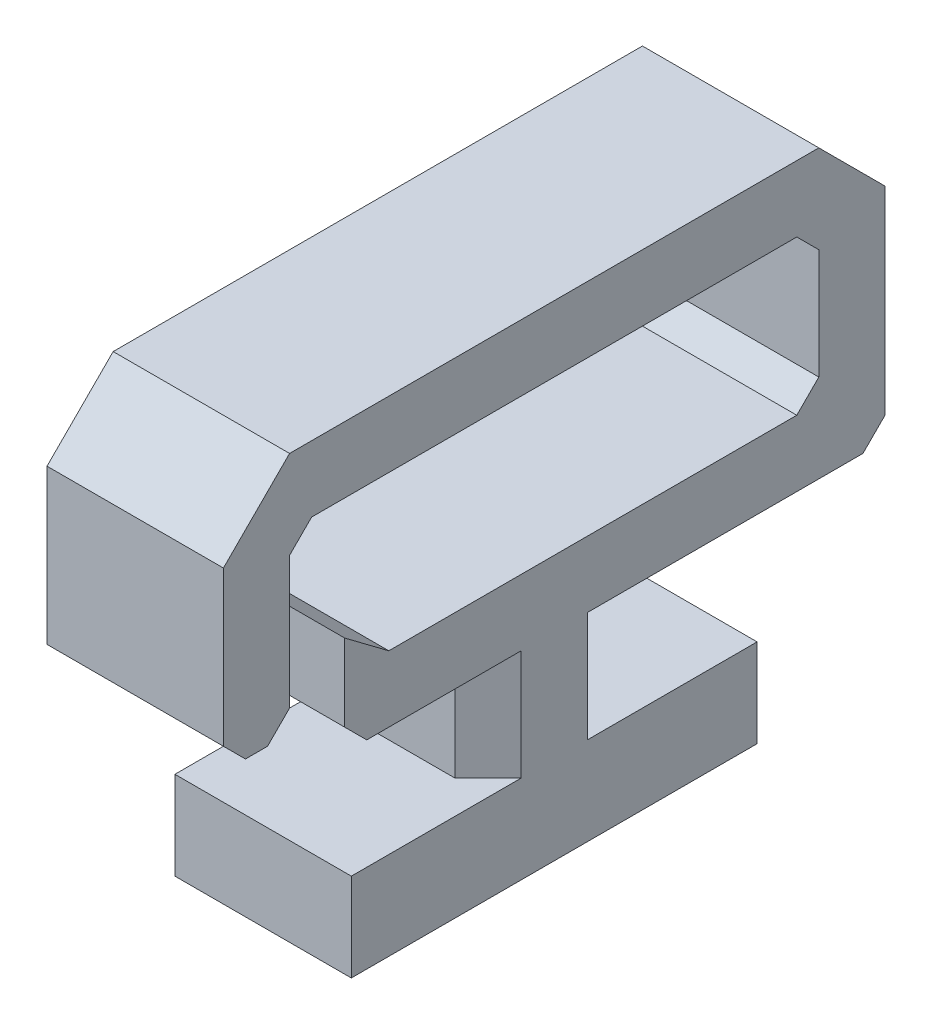
SolidWorks part; units mm, degrees
ref_plane "Front Plane" through (0, 0, 0) normal (0, 0, 1) x (1, 0, 0)
ref_plane "Top Plane" through (0, 0, 0) normal (0, 1, 0) x (1, 0, 0)
ref_plane "Right Plane" through (0, 0, 0) normal (1, 0, 0) x (0, 0, -1)
sketch "Sketch1" plane through (0, 0, 0) normal (1, 0, 0) x (0, 0, -1)
  line L0 (-4.6, 0) -> (4.6, 0)
  line L1 (-4.6, 0) -> (-4.6, 2)
  line L2 (-4.6, 2) -> (-1.5, 2)
  line L3 (4.6, 2) -> (4.6, 0)
  line L4 (0, 0) -> (0, 69.0546) construction
  line L5 (-1.5, 2) -> (-1.5, 4.5)
  line L6 (-6, 6) -> (-6, 4.5)
  line L7 (1.5, 4.5) -> (1.5, 2)
  line L8 (-1.5, 4.5) -> (-4.75, 4.5)
  line L9 (-7.5, 4.5) -> (-7.5, 11)
  line L10 (-7.5, 11) -> (7.5, 11)
  line L11 (7.5, 11) -> (7.5, 4.5)
  line L12 (7.5, 4.5) -> (1.5, 4.5)
  line L13 (-6, 9.5) -> (-6, 6)
  line L14 (-3.75, 6) -> (6, 6)
  line L15 (6, 6) -> (6, 9.5)
  line L16 (6, 9.5) -> (-6, 9.5)
  line L17 (-4.75, 6) -> (-4.75, 4.5)
  line L18 (-6, 6) -> (-4.75, 6) construction
  line L19 (1.5, 2) -> (4.6, 2)
  line L20 (-4.75, 4.5) -> (-6, 4.5) construction
  line L21 (-6, 4.5) -> (-7.5, 4.5)
  line L22 (-4.75, 6) -> (-4.75, 6.75)
  line L23 (-4.75, 6.75) -> (-3.75, 6)
  line L24 (-4.75, 6) -> (-3.75, 6) construction
  point P4 (0, 0)
  point P12 (0, 9.5)
  dimension "D1" = 9.2
  dimension "D2" = 2
  dimension "D3" = 3
  dimension "D4" = 2.5
  dimension "D5" = 12
  dimension "D6" = 1.25
  dimension "D7" = 1.5
  dimension "D8" = 1.5
  dimension "D9" = 1.5
  dimension "D10" = 1.5
  dimension "D11" = 3.5
  dimension "D12" = 1.5
  dimension "D13" = 0.75
  dimension "D14" = 1
extrude "Boss-Extrude1" add sketch "Sketch1" along normal blind 4
chamfer "Chamfer1" distance 0.75 angle 45 4 edges at (4, 3.25, -1.5) (4, 3.25, 1.5) (0, 3.25, -1.5) (0, 3.25, 1.5)
sketch "Sketch2" plane through (0, 0, 0) normal (-1, 0, 0) x (0, 0, 1)
  line L0 (6, 5.5) -> (7.5, 5.5)
  line L1 (6, 4.5) -> (6, 9.5) construction
  line L2 (7.5, 11) -> (7.5, 4.5) construction
  line L3 (7.5, 5.5) -> (7.5, 4.5)
  line L4 (7.5, 4.5) -> (6, 4.5)
  line L5 (6, 4.5) -> (6, 5.5)
  dimension "D1" = 1
extrude "Cut-Extrude1" cut sketch "Sketch2" against normal through all
chamfer "Chamfer2" distance 1.5 angle 45 2 edges at (2, 11, 7.5) (2, 11, -7.5)
chamfer "Chamfer3" distance 0.5 angle 45 7 edges at (2, 9.5, 6) (2, 9.5, -6) (2, 6, -6) (2, 4.5, -7.5) (2, 5.5, 7.5) (2, 4.5, 4.75) (2, 5.5, 6)
